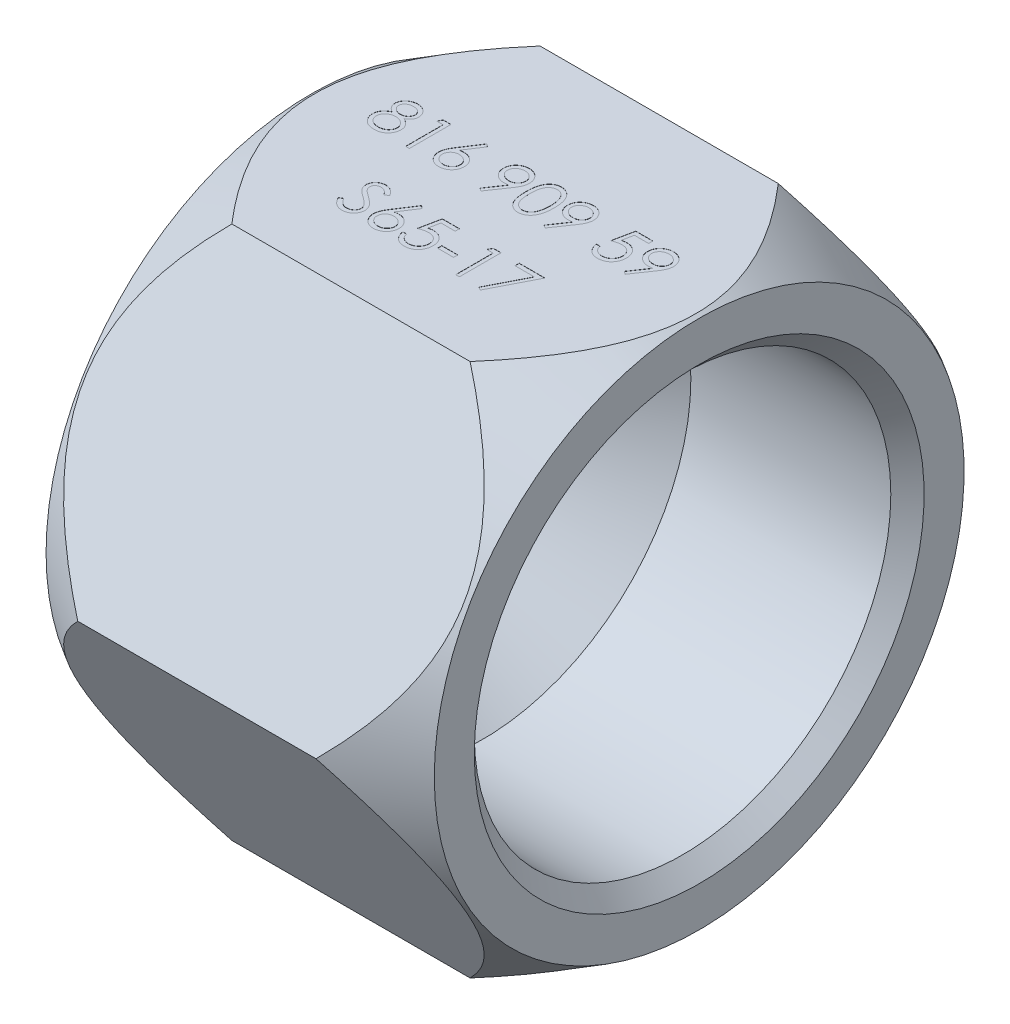
SolidWorks part; units mm, degrees
material "Plain Carbon Steel"
ref_plane "Front Plane" through (0, 0, 0) normal (0, 0, 1) x (1, 0, 0)
ref_plane "Top Plane" through (0, 0, 0) normal (0, 1, 0) x (1, 0, 0)
ref_plane "Right Plane" through (0, 0, 0) normal (1, 0, 0) x (0, 0, -1)
sketch "Sketch1" plane through (0, 0, 0) normal (0, 0, 1) x (1, 0, 0)
  line L0 (0, 0) -> (82.389, 0) construction
  line L1 (0, 0) -> (0, 15.9)
  line L2 (0, 15.9) -> (4.5, 18.5)
  line L3 (4.5, 18.5) -> (18.8, 18.5)
  line L4 (18.8, 18.5) -> (23.3, 15.9)
  line L5 (23.3, 15.9) -> (23.3, 12.5)
  line L6 (23.3, 12.5) -> (10.3, 12.5)
  line L7 (10.3, 12.5) -> (3.3, 7.2251)
  line L8 (3.3, 7.2251) -> (3.3, 0)
  line L9 (0, 0) -> (3.3, 0)
  dimension "D1" = 37
  dimension "D2" = 20
  dimension "D3" = 31.8
  dimension "D5" = 37
  dimension "D7" = 4.5
  dimension "D6" = 4.5
  dimension "D8" = 25
  dimension "D9" = 13
  dimension "D10" = 23.3
  dimension "D11" = 31.8
revolve "Revolve1" add sketch "Sketch1" angle 360 about L0
cosmetic thread "Cosmetic Thread1" parameters "D1"=10, "D2"=27
sketch "Sketch2" plane through (23.3, 0, 0) normal (1, 0, 0) x (0, 0, -1)
  line L1 (9.25, 16.0215) -> (-9.25, 16.0215)
  line L2 (-9.25, 16.0215) -> (-18.5, 0)
  line L3 (-18.5, 0) -> (-9.25, -16.0215)
  line L4 (-9.25, -16.0215) -> (9.25, -16.0215)
  line L5 (9.25, -16.0215) -> (18.5, 0)
  line L6 (18.5, 0) -> (9.25, 16.0215)
  circle A0 centre (0, 0) radius 16.0215 construction
  circle A1 centre (0, 0) radius 18.5 construction
extrude "Extrude1" cut sketch "Sketch2" against normal up to surface (23.3 mm away) flip side to cut up to face at (0, 0, 15.9)
chamfer "Chamfer1" distance 1 angle 45 1 edges at (23.3, 0, 12.5)
sketch "Sketch3" plane through (0, 16.0215, 0) normal (0, 1, 0) x (1, 0, 0)
  line L0 (0, 0) -> (23.0898, 0) construction
  spline S0 degree 3 poles (18.8, -9.25) (19.3656, -8.5964) (19.9119, -7.9133) (20.9163, -6.4987) (21.376, -5.7662) (21.9709, -4.6117) (22.1533, -4.2174) (22.4785, -3.4055) (22.6198, -2.9909) (22.8495, -2.1537) (22.9386, -1.7294) (23.059, -0.8684) (23.0901, -0.4281) (23.089, 0.8806) (22.9644, 1.7376) (22.616, 3.0032) (22.474, 3.4175) (22.1509, 4.2225) (21.9692, 4.6152) (21.5726, 5.3844) (21.3577, 5.7609) (20.9003, 6.5003) (20.6571, 6.8642) (19.9018, 7.9266) (19.3626, 8.5999) (18.8, 9.25) knots 0 0 0 0 0.125 0.125 0.25 0.25 0.3125 0.3125 0.375 0.375 0.4375 0.4375 0.5 0.5 0.625 0.625 0.6875 0.6875 0.75 0.75 0.8125 0.8125 0.875 0.875 1 1 1 1 construction
  text T0 "816 909 59\r\nS65-17"
extrude "Cut-Extrude1" cut sketch "Sketch3" against normal blind 0.01
